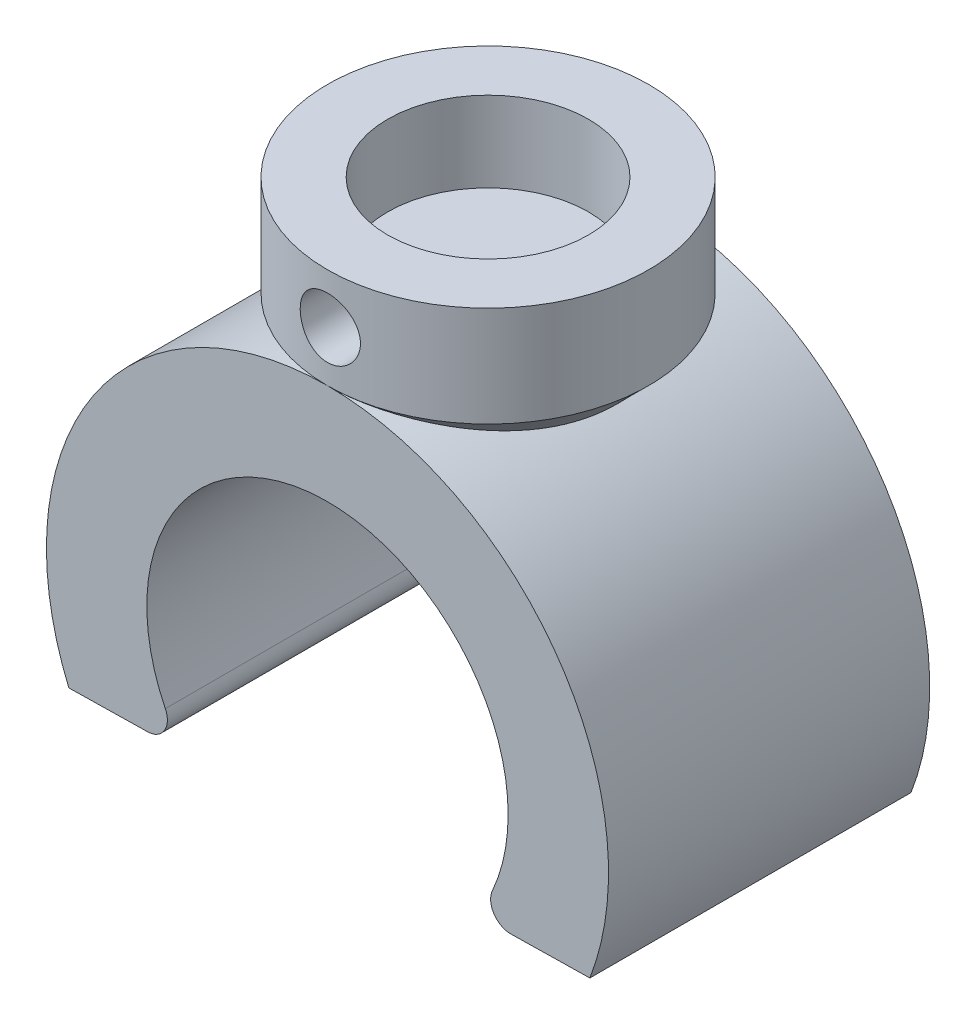
SolidWorks part; units mm, degrees
ref_plane "Front Plane" through (0, 0, 0) normal (0, 0, 1) x (1, 0, 0)
ref_plane "Top Plane" through (0, 0, 0) normal (0, 1, 0) x (1, 0, 0)
ref_plane "Right Plane" through (0, 0, 0) normal (1, 0, 0) x (0, 0, -1)
sketch "Sketch1" plane through (0, 0, 0) normal (0, 0, 1) x (1, 0, 0)
  circle A0 centre (0, 0) radius 14
extrude "Boss-Extrude1" add sketch "Sketch1" along normal blind 16 contours A0
sketch "Sketch2" plane through (0, 0, 16) normal (0, 0, 1) x (1, 0, 0)
  circle A0 centre (0, 0) radius 9
extrude "Cut-Extrude1" cut sketch "Sketch2" against normal up to next
sketch "Sketch3" plane through (0, 0, 16) normal (0, 0, 1) x (1, 0, 0)
  line L1 (-14, -5.5) -> (14, -5)
  line L2 (-14, -5.5) -> (-14, -14)
  line L3 (-14, -14) -> (14, -14)
  line L4 (14, -5) -> (14, -14)
  line L5 (-14, -5.5) -> (14, -14) construction
  line L6 (-14, -14) -> (14, -5) construction
  point P4 (0, -11.7517)
  point P5 (0, 0)
  point P6 (0, 0)
  point P7 (0, 0)
  point P8 (0, 0)
  point P9 (0, 0)
  point P10 (0, 0)
  point P11 (0, 0)
  point P12 (0, 0)
  point P13 (0, 0)
extrude "Cut-Extrude2" cut sketch "Sketch3" against normal through all
sketch "Sketch4" plane through (0, 0, 0) normal (0, 1, 0) x (-1, 0, 0)
  circle A0 centre (0, 8) radius 5
extrude "Boss-Extrude2" add sketch "Sketch4" along normal blind 3 draft 45 from offset 11 draft outward yes
sketch "Sketch5" plane through (0, 14, 0) normal (0, 1, 0) x (1, 0, 0)
  circle A0 centre (0, -8) radius 8
extrude "Boss-Extrude3" add sketch "Sketch5" along normal blind 5
sketch "Sketch6" plane through (0, 19, 0) normal (0, 1, 0) x (1, 0, 0)
  circle A0 centre (0, -8) radius 5
extrude "Cut-Extrude3" cut sketch "Sketch6" against normal blind 4
sketch "Sketch7" plane through (0, 0, 0) normal (0, 0, 1) x (1, 0, 0)
  circle A0 centre (0, 16.5) radius 1.5
extrude "Cut-Extrude4" cut sketch "Sketch7" against normal blind 5 from offset 17
fillet "Fillet1" radius 1 2 edges at (-7.2158, -5.3789, 8) (7.4033, -5.1178, 8)
